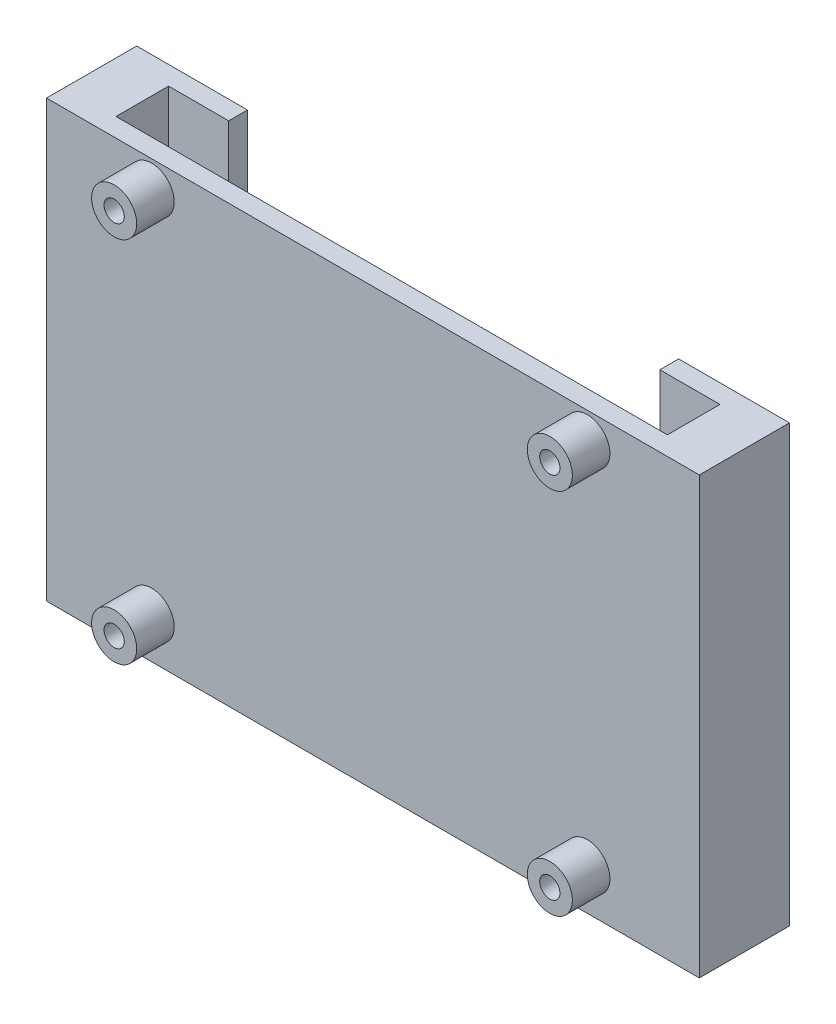
SolidWorks part; units mm, degrees
material "eSUN Tough Resin"
ref_plane "Front Plane" through (0, 0, 0) normal (0, 0, 1) x (1, 0, 0)
ref_plane "Top Plane" through (0, 0, 0) normal (0, 1, 0) x (1, 0, 0)
ref_plane "Right Plane" through (0, 0, 0) normal (1, 0, 0) x (0, 0, -1)
sketch "Sketch1" plane through (0, 0, 0) normal (0, 0, 1) x (1, 0, 0)
  line L1 (-43.45, -29) -> (43.45, -29)
  line L2 (-43.45, -29) -> (-43.45, 29)
  line L3 (-43.45, 29) -> (43.45, 29)
  line L4 (43.45, -29) -> (43.45, 29)
  line L5 (-43.45, -29) -> (43.45, 29) construction
  line L6 (-43.45, 29) -> (43.45, -29) construction
  point P0 (0, 0)
  dimension "D1" = 86.9
  dimension "D2" = 58
extrude "Boss-Extrude1" add sketch "Sketch1" along normal blind 2.5
sketch "Sketch2" plane through (0, 0, 2.5) normal (0, 0, 1) x (1, 0, 0)
  line L0 (43.45, 29) -> (-43.45, 29) construction
  line L1 (-43.45, 29) -> (-43.45, -29) construction
  circle A0 centre (-29.45, 25.5) radius 3
  circle A1 centre (28.55, 25.5) radius 3
  dimension "D1" = 6
  dimension "D4" = 58
  dimension "D2" = 3.5
  dimension "D3" = 14
extrude "Boss-Extrude2" add sketch "Sketch2" along normal blind 5
pattern_linear "LPattern1" count 2 spacing 49 along (0, -1, 0) of "Boss-Extrude2"
hole_wizard "M2.5 Clearance Hole1" positions "Sketch3" profile "Sketch4" hole size "M2.5" standard "ANSI Metric" end condition through all
sketch "Sketch3" plane through (0, 0, 7.5) normal (0, 0, 1) x (1, 0, 0)
  circle A0 centre (-29.45, -23.5) radius 3 construction
  circle A1 centre (28.55, 25.5) radius 3 construction
  circle A2 centre (28.55, -23.5) radius 3 construction
  point P0 (-29.45, 25.5)
  point P3 (-29.45, -23.5)
  point P10 (28.55, 25.5)
  point P12 (28.55, -23.5)
sketch "Sketch4" plane through (-29.45, 25.5, 7.5) normal (1, 0, 0) x (0, -1, 0)
  line L0 (0, 0) -> (0, 7.5)
  line L1 (0, 7.5) -> (1.35, 7.5)
  line L2 (1.35, 7.5) -> (1.35, 0)
  line L5 (1.35, 0) -> (0, 0)
  line L11 (0, -6.35) -> (0, 107.95) construction
  dimension "Thru Hole Dia." = 2.7
  dimension "Thru Hole Depth" = 7.5
sketch "Sketch6" plane through (0, 0, 0) normal (0, 0, -1) x (-1, 0, 0)
  line L0 (43.45, -29) -> (-43.45, -29) construction
  line L1 (-43.45, 29) -> (-36.7, 29)
  line L2 (-43.45, 29) -> (-43.45, -29)
  line L3 (-43.45, -29) -> (-36.7, -29)
  line L4 (-36.7, 29) -> (-36.7, -29)
  line L6 (43.45, 29) -> (36.7, 29)
  line L7 (43.45, 29) -> (43.45, -29)
  line L8 (43.45, -29) -> (36.7, -29)
  line L9 (36.7, 29) -> (36.7, -29)
  dimension "D1" = 6.75
  dimension "D2" = 6.75
extrude "Boss-Extrude3" add sketch "Sketch6" along normal blind 9.5
sketch "Sketch7" plane through (36.7, 0, 0) normal (-1, 0, 0) x (0, 0, 1)
  line L0 (2.5, -29) -> (-9.5, -29) construction
  line L1 (-9.5, 29) -> (-7, 29)
  line L2 (-9.5, 29) -> (-9.5, -29)
  line L3 (-9.5, -29) -> (-7, -29)
  line L4 (-7, 29) -> (-7, -29)
  dimension "D1" = 2.5
extrude "Boss-Extrude4" add sketch "Sketch7" along normal blind 8
sketch "Sketch8" plane through (-36.7, 0, 0) normal (1, 0, 0) x (0, 0, -1)
  line L1 (9.5, 29) -> (7, 29)
  line L2 (9.5, 29) -> (9.5, -29)
  line L3 (9.5, -29) -> (7, -29)
  line L4 (7, 29) -> (7, -29)
extrude "Boss-Extrude5" add sketch "Sketch8" along normal blind 8
sketch "Sketch9" plane through (0, -29, 0) normal (0, -1, 0) x (1, 0, 0)
  line L0 (-43.45, -3.5) -> (43.45, -3.5) construction
  line L1 (-43.45, 2.5) -> (-43.45, -9.5) construction
  line L2 (43.45, 2.5) -> (43.45, -9.5) construction
  line L3 (-36.7, 0) -> (-43.45, 0) construction
  line L4 (-40.075, 0) -> (-40.075, -9.5) construction
  line L5 (-28.7, -9.5) -> (-43.45, -9.5) construction
  line L6 (36.7, 0) -> (43.45, 0) construction
  line L7 (40.075, 0) -> (40.075, -9.5) construction
  line L8 (43.45, -9.5) -> (28.7, -9.5) construction
  circle A0 centre (-40.075, -3.5) radius 3.15
  circle A1 centre (40.075, -3.5) radius 3.15
  dimension "D1" = 6.3
  dimension "D2" = 6.3
extrude "Cut-Extrude1" cut sketch "Sketch9" against normal blind 2.7
